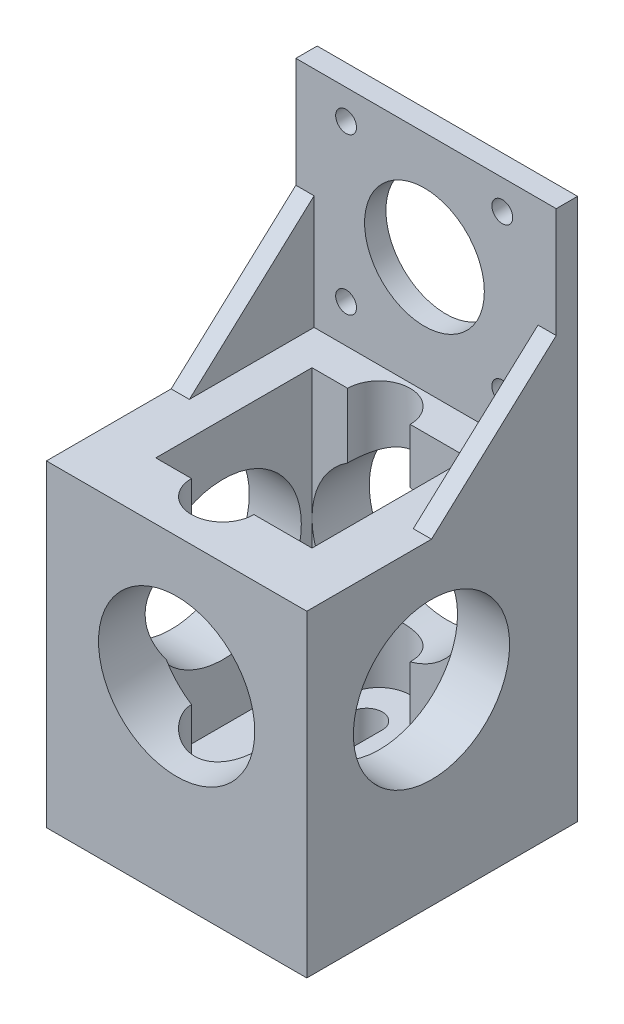
SolidWorks part; units mm, degrees
ref_plane "Front Plane" through (0, 0, 0) normal (0, 0, 1) x (1, 0, 0)
ref_plane "Top Plane" through (0, 0, 0) normal (0, 1, 0) x (1, 0, 0)
ref_plane "Right Plane" through (0, 0, 0) normal (1, 0, 0) x (0, 0, -1)
sketch "Sketch1" plane through (0, 0, 0) normal (0, 1, 0) x (1, 0, 0)
  line L1 (-25, 26) -> (25, 26)
  line L2 (-25, 26) -> (-25, -26)
  line L3 (-25, -26) -> (25, -26)
  line L4 (25, 26) -> (25, -26)
  line L5 (0, -26) -> (0, 26) construction
  line L6 (-25, 0) -> (25, 0) construction
  point P0 (0, 0)
  dimension "D1" = 52
  dimension "D2" = 50
extrude "Boss-Extrude1" add sketch "Sketch1" along normal blind 61
sketch "Sketch2" plane through (0, 61, 0) normal (0, 1, 0) x (1, 0, 0)
  line L1 (-15, 15) -> (15, 15)
  line L2 (-15, 15) -> (-15, -15)
  line L3 (-15, -15) -> (15, -15)
  line L4 (15, 15) -> (15, -15)
  line L5 (0, -15) -> (0, 15) construction
  line L6 (-15, 0) -> (15, 0) construction
  point P0 (0, 0)
  dimension "D1" = 30
  dimension "D2" = 30
extrude "Cut-Extrude1" cut sketch "Sketch2" against normal blind 51
sketch "Sketch3" plane through (0, 10, 0) normal (0, 1, 0) x (1, 0, 0)
  line L4 (-2, 12.5) -> (-2, -12.5) construction
  line L5 (1, 12.5) -> (1, -12.5)
  line L6 (-5, 12.5) -> (-5, -12.5)
  arc A0 (1, 12.5) -> (-5, 12.5) centre (-2, 12.5) ccw
  arc A1 (-5, -12.5) -> (1, -12.5) centre (-2, -12.5) ccw
  point P11 (-2, 0)
  dimension "D1" = 25
  dimension "D2" = 6
extrude "Cut-Extrude2" cut sketch "Sketch3" against normal mid plane 150
sketch "Sketch5" plane through (0, 61, 0) normal (0, 1, 0) x (1, 0, 0)
  line L1 (-2.1471, 15) -> (-2.1471, -15) construction
  line L2 (3.8529, 15) -> (3.8529, -15)
  line L3 (-8.1471, 15) -> (-8.1471, -15)
  arc A2 (3.8529, 15) -> (-8.1471, 15) centre (-2.1471, 15) ccw
  arc A3 (-8.1471, -15) -> (3.8529, -15) centre (-2.1471, -15) ccw
  point P0 (-2.1471, 0)
  point P10 (-2.1471, 0)
  dimension "D1" = 12
  dimension "D2" = 30
extrude "Cut-Extrude3" cut sketch "Sketch5" against normal blind 51
sketch "Sketch6" plane through (0, 61, 0) normal (0, 1, 0) x (1, 0, 0)
  line L0 (25, -26) -> (25, 26) construction
  line L1 (-25, 26) -> (25, 26)
  line L2 (-25, 26) -> (-25, 21.9)
  line L3 (-25, 21.9) -> (25, 21.9)
  line L4 (25, 26) -> (25, 21.9)
  dimension "D1" = 4.1
extrude "Boss-Extrude2" add sketch "Sketch6" along normal blind 43
sketch "Sketch8" plane through (0, 0, -21.9) normal (0, 0, 1) x (1, 0, 0)
  circle A0 centre (-0.3059, 83.2776) radius 11.5
  circle A3 centre (-15.3559, 68.3276) radius 2
  circle A4 centre (-15.3559, 98.3276) radius 2
  circle A5 centre (14.6441, 68.3276) radius 2
  circle A6 centre (14.6441, 98.3276) radius 2
  point P5 (-0.3059, 83.2776)
  dimension "D1" = 30
extrude "Cut-Extrude4" cut sketch "Sketch8" against normal blind 43
sketch "Sketch9" plane through (-25, 0, 0) normal (-1, 0, 0) x (0, 0, 1)
  line L0 (-21.9, 61) -> (2.05, 61)
  line L1 (-21.9, 61) -> (26, 61) construction
  line L2 (2.05, 61) -> (-21.9, 82.8939)
  line L3 (-21.9, 104) -> (-21.9, 61) construction
  line L4 (-21.9, 82.8939) -> (-21.9, 61)
extrude "Boss-Extrude3" add sketch "Sketch9" against normal blind 3.5
sketch "Sketch10" plane through (25, 0, 0) normal (1, 0, 0) x (0, 0, -1)
  line L0 (21.9, 61) -> (-2.05, 61)
  line L1 (-2.05, 61) -> (21.9, 82.8939)
  line L2 (21.9, 82.8939) -> (21.9, 61)
extrude "Boss-Extrude4" add sketch "Sketch10" against normal blind 3.5
sketch "Sketch11" plane through (0, 0, 26) normal (0, 0, 1) x (1, 0, 0)
  circle A0 centre (0, 36) radius 15
  point P6 (0, 36.0482)
extrude "Cut-Extrude5" cut sketch "Sketch11" against normal blind 98.5
sketch "Sketch12" plane through (25, 0, 0) normal (1, 0, 0) x (0, 0, -1)
  circle A0 centre (-2.05, 36) radius 15
extrude "Cut-Extrude6" cut sketch "Sketch12" against normal blind 98.5
